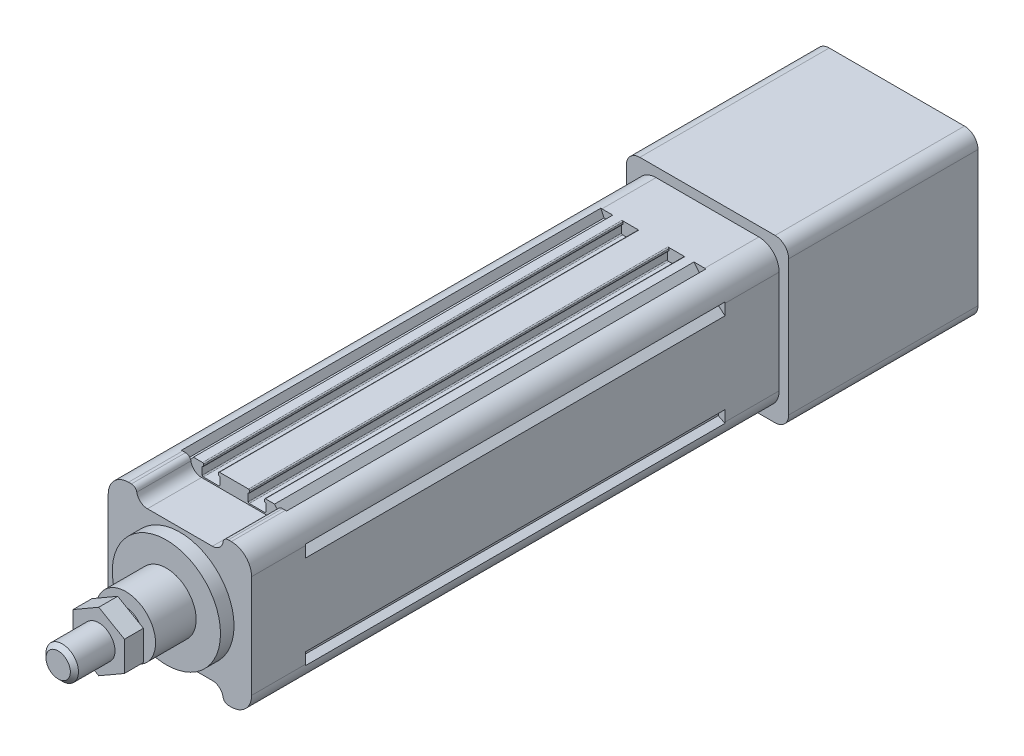
SolidWorks part; units mm, degrees
ref_plane "Front" through (0, 0, 0) normal (0, 0, 1) x (1, 0, 0)
ref_plane "Top" through (0, 0, 0) normal (0, 1, 0) x (1, 0, 0)
ref_plane "Right" through (0, 0, 0) normal (1, 0, 0) x (0, 0, -1)
sketch "草图1" plane through (0, 0, 0) normal (0, 0, 1) x (1, 0, 0)
  line L0 (19.7737, 3) -> (23.3, 3)
  line L1 (23.3, 3) -> (23.3, -3)
  line L2 (23.3, -3) -> (19.7737, -3)
  line L3 (-19.7737, -3) -> (-23.3, -3)
  line L4 (-23.3, -3) -> (-23.3, 3)
  line L5 (-23.3, 3) -> (-19.7737, 3)
  line L6 (-18.2, 24) -> (-19.4434, 26.4869)
  line L7 (-26.4869, 19.4434) -> (-24, 18.2)
  line L8 (-24, 18.2) -> (-24, 17.1)
  line L9 (-24, 17.1) -> (-26.5, 15)
  line L10 (-26.5, 15) -> (-26.5, -15)
  line L11 (-26.5, -15) -> (-24, -17.1)
  line L12 (-24, -17.1) -> (-24, -18.2)
  line L13 (-24, -18.2) -> (-26.4869, -19.4434)
  line L14 (-19.4434, -26.4869) -> (-18.2, -24)
  line L15 (-18.2, -24) -> (-17.1, -24)
  line L16 (-17.1, -24) -> (-15, -26.5)
  line L17 (-15, -26.5) -> (-11.65, -26.5)
  line L18 (-11.25, -26.1) -> (-11.25, -25.6)
  line L19 (-11.65, -25.2) -> (-11.75, -25.2)
  line L20 (-11.75, -25.2) -> (-11.75, -22.4)
  line L21 (-11.35, -22) -> (-5.65, -22)
  line L22 (-5.25, -22.4) -> (-5.25, -25.2)
  line L23 (-5.25, -25.2) -> (-5.35, -25.2)
  line L24 (-5.75, -25.6) -> (-5.75, -26.1)
  line L25 (-5.35, -26.5) -> (5.35, -26.5)
  line L26 (5.75, -26.1) -> (5.75, -25.6)
  line L27 (5.35, -25.2) -> (5.25, -25.2)
  line L28 (5.25, -25.2) -> (5.25, -22.4)
  line L29 (5.65, -22) -> (11.35, -22)
  line L30 (11.75, -22.4) -> (11.75, -25.2)
  line L31 (11.75, -25.2) -> (11.65, -25.2)
  line L32 (11.25, -25.6) -> (11.25, -26.1)
  line L33 (11.65, -26.5) -> (15, -26.5)
  line L34 (15, -26.5) -> (17.1, -24)
  line L35 (17.1, -24) -> (18.2, -24)
  line L36 (18.2, -24) -> (19.4434, -26.4869)
  line L37 (26.4869, -19.4434) -> (24, -18.2)
  line L38 (24, -18.2) -> (24, -17.1)
  line L39 (24, -17.1) -> (26.5, -15)
  line L40 (26.5, -15) -> (26.5, 15)
  line L41 (26.5, 15) -> (24, 17.1)
  line L42 (24, 17.1) -> (24, 18.2)
  line L43 (24, 18.2) -> (26.4869, 19.4434)
  line L44 (19.4434, 26.4869) -> (18.2, 24)
  line L45 (18.2, 24) -> (17.1, 24)
  line L46 (17.1, 24) -> (15, 26.5)
  line L47 (15, 26.5) -> (11.65, 26.5)
  line L48 (11.25, 26.1) -> (11.25, 25.6)
  line L49 (11.65, 25.2) -> (11.75, 25.2)
  line L50 (11.75, 25.2) -> (11.75, 22.4)
  line L51 (11.35, 22) -> (5.65, 22)
  line L52 (5.25, 22.4) -> (5.25, 25.2)
  line L53 (5.25, 25.2) -> (5.35, 25.2)
  line L54 (5.75, 25.6) -> (5.75, 26.1)
  line L55 (5.35, 26.5) -> (-5.35, 26.5)
  line L56 (-5.75, 26.1) -> (-5.75, 25.6)
  line L57 (-5.35, 25.2) -> (-5.25, 25.2)
  line L58 (-5.25, 25.2) -> (-5.25, 22.4)
  line L59 (-5.65, 22) -> (-11.35, 22)
  line L60 (-11.75, 22.4) -> (-11.75, 25.2)
  line L61 (-11.75, 25.2) -> (-11.65, 25.2)
  line L62 (-11.25, 25.6) -> (-11.25, 26.1)
  line L63 (-11.65, 26.5) -> (-15, 26.5)
  line L64 (-15, 26.5) -> (-17.1, 24)
  line L65 (-17.1, 24) -> (-18.2, 24)
  arc A0 (19.7737, 3) -> (-19.7737, 3) centre (0, 0) ccw
  arc A1 (-19.7737, -3) -> (19.7737, -3) centre (0, 0) ccw
  circle A2 centre (19, 19) radius 2.1
  circle A3 centre (19, -19) radius 2.1
  circle A4 centre (-19, -19) radius 2.1
  circle A5 centre (-19, 19) radius 2.1
  arc A6 (-19.4434, 26.4869) -> (-26.4869, 19.4434) centre (-19, 19) ccw
  arc A7 (-26.4869, -19.4434) -> (-19.4434, -26.4869) centre (-19, -19) ccw
  arc A8 (-11.65, -26.5) -> (-11.25, -26.1) centre (-11.65, -26.1) ccw
  arc A9 (-11.25, -25.6) -> (-11.65, -25.2) centre (-11.65, -25.6) ccw
  arc A10 (-11.35, -22) -> (-11.75, -22.4) centre (-11.35, -22.4) ccw
  arc A11 (-5.25, -22.4) -> (-5.65, -22) centre (-5.65, -22.4) ccw
  arc A12 (-5.35, -25.2) -> (-5.75, -25.6) centre (-5.35, -25.6) ccw
  arc A13 (-5.75, -26.1) -> (-5.35, -26.5) centre (-5.35, -26.1) ccw
  arc A14 (5.35, -26.5) -> (5.75, -26.1) centre (5.35, -26.1) ccw
  arc A15 (5.75, -25.6) -> (5.35, -25.2) centre (5.35, -25.6) ccw
  arc A16 (5.65, -22) -> (5.25, -22.4) centre (5.65, -22.4) ccw
  arc A17 (11.75, -22.4) -> (11.35, -22) centre (11.35, -22.4) ccw
  arc A18 (11.65, -25.2) -> (11.25, -25.6) centre (11.65, -25.6) ccw
  arc A19 (11.25, -26.1) -> (11.65, -26.5) centre (11.65, -26.1) ccw
  arc A20 (19.4434, -26.4869) -> (26.4869, -19.4434) centre (19, -19) ccw
  arc A21 (26.4869, 19.4434) -> (19.4434, 26.4869) centre (19, 19) ccw
  arc A22 (11.65, 26.5) -> (11.25, 26.1) centre (11.65, 26.1) ccw
  arc A23 (11.25, 25.6) -> (11.65, 25.2) centre (11.65, 25.6) ccw
  arc A24 (11.35, 22) -> (11.75, 22.4) centre (11.35, 22.4) ccw
  arc A25 (5.25, 22.4) -> (5.65, 22) centre (5.65, 22.4) ccw
  arc A26 (5.35, 25.2) -> (5.75, 25.6) centre (5.35, 25.6) ccw
  arc A27 (5.75, 26.1) -> (5.35, 26.5) centre (5.35, 26.1) ccw
  arc A28 (-5.35, 26.5) -> (-5.75, 26.1) centre (-5.35, 26.1) ccw
  arc A29 (-5.75, 25.6) -> (-5.35, 25.2) centre (-5.35, 25.6) ccw
  arc A30 (-5.65, 22) -> (-5.25, 22.4) centre (-5.65, 22.4) ccw
  arc A31 (-11.75, 22.4) -> (-11.35, 22) centre (-11.35, 22.4) ccw
  arc A32 (-11.65, 25.2) -> (-11.25, 25.6) centre (-11.65, 25.6) ccw
  arc A33 (-11.25, 26.1) -> (-11.65, 26.5) centre (-11.65, 26.1) ccw
extrude "凸台-拉伸1" add sketch "草图1" along normal blind 155
sketch "草图6" plane through (0, 0, 155) normal (0, 0, 1) x (1, 0, 0)
  line L0 (0, 0) -> (19, 0) construction
  line L2 (-26.5, -19) -> (-26.5, 19)
  line L3 (-19, 26.5) -> (-17.9161, 26.5)
  line L4 (26.5, -19) -> (26.5, 19)
  line L5 (-26.5, -26.5) -> (26.5, 26.5) construction
  line L6 (-26.5, 26.5) -> (26.5, -26.5) construction
  line L7 (-12, 21.5) -> (12, 21.5)
  line L9 (19, 26.5) -> (17.9161, 26.5)
  line L10 (19, -26.5) -> (17.9161, -26.5)
  line L11 (-12, -21.5) -> (12, -21.5)
  line L12 (-19, -26.5) -> (-17.9161, -26.5)
  arc A0 (12, 21.5) -> (15.9441, 24.8333) centre (12, 25.5) ccw
  arc A1 (-15.9441, 24.8333) -> (-12, 21.5) centre (-12, 25.5) ccw
  arc A2 (-15.9441, 24.8333) -> (-17.9161, 26.5) centre (-17.9161, 24.5) ccw
  arc A3 (15.9441, 24.8333) -> (17.9161, 26.5) centre (17.9161, 24.5) cw
  arc A4 (-26.5, -19) -> (-19, -26.5) centre (-19, -19) ccw
  arc A5 (19, -26.5) -> (26.5, -19) centre (19, -19) ccw
  arc A6 (26.5, 19) -> (19, 26.5) centre (19, 19) ccw
  arc A7 (-26.5, 19) -> (-19, 26.5) centre (-19, 19) cw
  arc A8 (15.9441, -24.8333) -> (17.9161, -26.5) centre (17.9161, -24.5) ccw
  arc A9 (12, -21.5) -> (15.9441, -24.8333) centre (12, -25.5) cw
  arc A10 (-15.9441, -24.8333) -> (-12, -21.5) centre (-12, -25.5) cw
  arc A11 (-15.9441, -24.8333) -> (-17.9161, -26.5) centre (-17.9161, -24.5) cw
  point P0 (0, 0)
  point P9 (0, 21.5)
  point P13 (20, 20.8461)
  point P16 (-12, 20.8461)
  dimension "D5" = 4
  dimension "D6" = 2
  dimension "D7" = 2
  dimension "D9" = 7.5
  dimension "D1" = 53
  dimension "D2" = 53
  dimension "D3" = 26.5
  dimension "D4" = 24
  dimension "D8" = 5
extrude "凸台-拉伸2" add sketch "草图6" along normal blind 20
sketch "草图7" plane through (0, 0, 175) normal (0, 0, 1) x (1, 0, 0)
  circle A0 centre (0, 0) radius 20
  dimension "D1" = 40
extrude "凸台-拉伸3" add sketch "草图7" along normal blind 5
sketch "草图9" plane through (0, 0, 180) normal (0, 0, 1) x (1, 0, 0)
  circle A0 centre (0, 0) radius 11
  dimension "D1" = 22
extrude "凸台-拉伸4" add sketch "草图9" along normal blind 15
sketch "草图10" plane through (0, 0, 195) normal (0, 0, 1) x (1, 0, 0)
  circle A0 centre (0, 0) radius 6
  dimension "D1" = 12
extrude "凸台-拉伸5" add sketch "草图10" along normal blind 25
sketch "草图11" plane through (0, 0, 0) normal (0, 0, -1) x (-1, 0, 0)
  line L1 (-19, -26.5) -> (19, -26.5)
  line L2 (-26.5, -19) -> (-26.5, 19)
  line L3 (-19, 26.5) -> (19, 26.5)
  line L4 (26.5, -19) -> (26.5, 19)
  line L5 (-26.5, -26.5) -> (26.5, 26.5) construction
  line L6 (-26.5, 26.5) -> (26.5, -26.5) construction
  arc A0 (-26.5, -19) -> (-19, -26.5) centre (-19, -19) ccw
  arc A1 (19, -26.5) -> (26.5, -19) centre (19, -19) ccw
  arc A2 (26.5, 19) -> (19, 26.5) centre (19, 19) ccw
  arc A3 (-26.5, 19) -> (-19, 26.5) centre (-19, 19) cw
  point P0 (0, 0)
  dimension "D3" = 7.5
  dimension "D1" = 53
  dimension "D2" = 53
extrude "凸台-拉伸6" add sketch "草图11" along normal blind 20
sketch "草图12" plane through (0, 0, -20) normal (0, 0, -1) x (-1, 0, 0)
  line L1 (-25, -30) -> (25, -30)
  line L2 (-30, -25) -> (-30, 25)
  line L3 (-25, 30) -> (25, 30)
  line L4 (30, -25) -> (30, 25)
  line L5 (-30, -30) -> (30, 30) construction
  line L6 (-30, 30) -> (30, -30) construction
  arc A0 (-30, -25) -> (-25, -30) centre (-25, -25) ccw
  arc A1 (25, -30) -> (30, -25) centre (25, -25) ccw
  arc A2 (30, 25) -> (25, 30) centre (25, 25) ccw
  arc A3 (-30, 25) -> (-25, 30) centre (-25, 25) cw
  point P0 (0, 0)
  dimension "D3" = 5
  dimension "D1" = 60
  dimension "D2" = 60
extrude "凸台-拉伸7" add sketch "草图12" along normal blind 70
sketch "草图14" plane through (0, 0, -90) normal (0, 0, -1) x (-1, 0, 0)
  circle A0 centre (0, 0) radius 19
  dimension "D1" = 38
extrude "切除-拉伸2" cut sketch "草图14" against normal blind 70
hole_wizard "M6 螺纹孔1" positions "草图15" profile "草图16" tap size "M6" standard "GB"
sketch "草图15" plane through (-26.5, 0, 0) normal (-1, 0, 0) x (0, 0, 1)
  line L0 (-20, -25) -> (-20, 25) construction
  line L1 (175, 19) -> (175, -19) construction
  point P0 (165, 11)
  point P2 (165, -11)
  point P4 (-10, 11)
  point P6 (-10, -11)
  dimension "D1" = 10
  dimension "D2" = 10
  dimension "D3" = 11
  dimension "D4" = 11
  dimension "D5" = 10
  dimension "D6" = 10
  dimension "D7" = 22
  dimension "D8" = 11
sketch "草图16" plane through (-26.5, 11, 165) normal (0, 1, 0) x (0, 0, 1)
  line L0 (0, 0) -> (0, 16.5022)
  line L1 (0, 16.5022) -> (2.5, 15)
  line L2 (2.5, 15) -> (2.5, 0)
  line L5 (2.5, 0) -> (0, 0)
  line L10 (0, 16.5022) -> (-2.5, 15) construction
  line L11 (0, -6.35) -> (0, 107.95) construction
  dimension "螺纹孔钻头直径" = 5
  dimension "螺纹孔钻头深度" = 15
  dimension "导头角度" = 118
cosmetic thread "孔螺蚊线4" parameters "D1"=12, "D2"=6
cosmetic thread "孔螺蚊线5" parameters "D1"=12, "D2"=6
cosmetic thread "孔螺蚊线6" parameters "D1"=12, "D2"=6
cosmetic thread "孔螺蚊线7" parameters "D1"=12, "D2"=6
chamfer "倒角1" distance 1.5 angle 45 1 edges at (6, 0, 220)
sketch "草图17" plane through (0, 0, 195) normal (0, 0, 1) x (1, 0, 0)
  line L1 (0, 10.9697) -> (-9.5, 5.4848)
  line L2 (-9.5, 5.4848) -> (-9.5, -5.4848)
  line L3 (-9.5, -5.4848) -> (0, -10.9697)
  line L4 (0, -10.9697) -> (9.5, -5.4848)
  line L5 (9.5, -5.4848) -> (9.5, 5.4848)
  line L6 (9.5, 5.4848) -> (0, 10.9697)
  circle A0 centre (0, 0) radius 9.5 construction
  dimension "D1" = 19
extrude "凸台-拉伸8" add sketch "草图17" along normal blind 7 from offset 3
